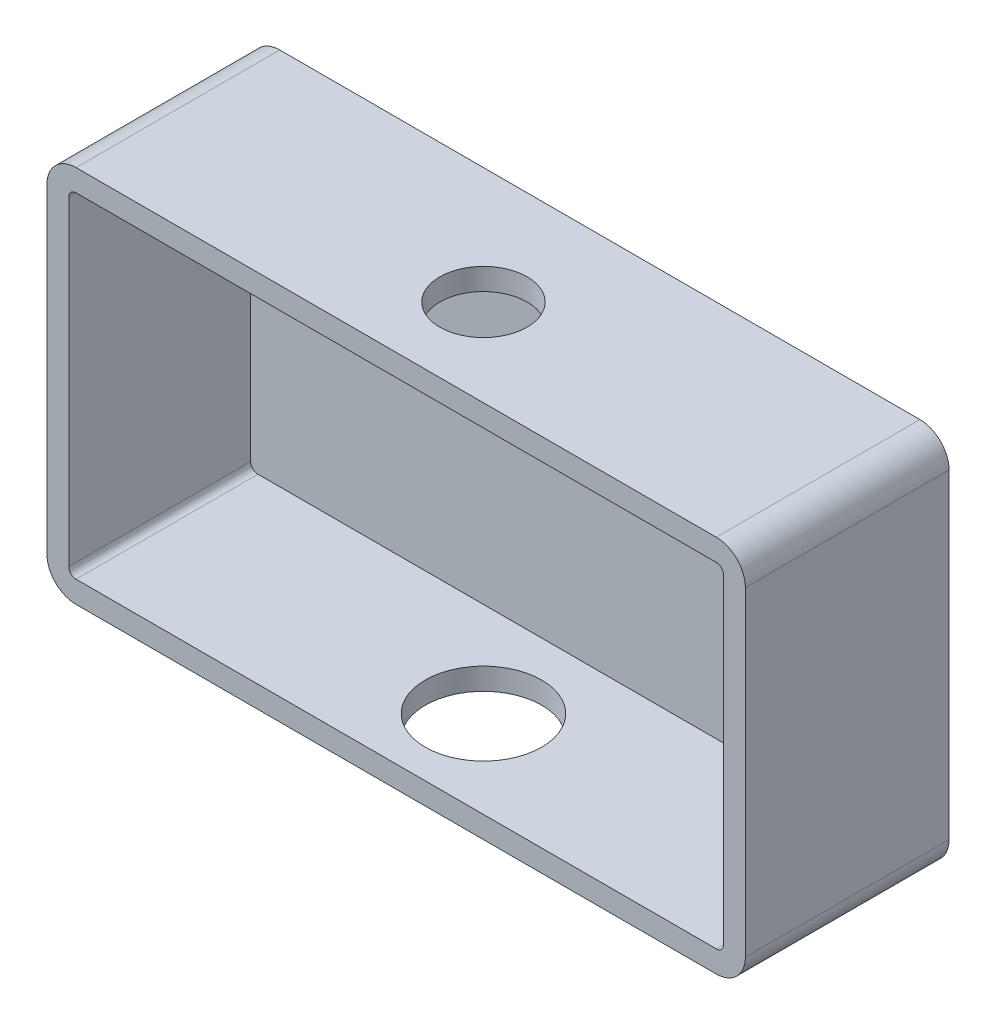
SolidWorks part; units mm, degrees
ref_plane "前视基准面" through (0, 0, 0) normal (0, 0, 1) x (1, 0, 0)
ref_plane "上视基准面" through (0, 0, 0) normal (0, 1, 0) x (1, 0, 0)
ref_plane "右视基准面" through (0, 0, 0) normal (1, 0, 0) x (0, 0, -1)
other "Configuration Table"
sketch "草图1" plane through (0, 0, 0) normal (0, 0, 1) x (1, 0, 0)
  line L0 (0, 0) -> (48, 0)
  line L1 (48, 0) -> (48, 26)
  line L2 (48, 26) -> (0, 26)
  line L3 (0, 26) -> (0, 0)
  dimension "width" = 48
  dimension "height" = 26
extrude "Enclosure" add sketch "草图1" along normal blind 14
fillet "Fillet" radius 2 4 edges at (0, 26, 7) (48, 26, 7) (48, 0, 7) (0, 0, 7)
shell "抽壳1" thickness 1.5
sketch "草图2" plane through (0, 0, 0) normal (0, -1, 0) x (1, 0, 0)
  circle A0 centre (24, 8) radius 3
  dimension "diameter" = 6
  dimension "x" = 24
  dimension "y" = 8
extrude "Cable_entry" cut sketch "草图2" against normal through all
sketch "草图3" plane through (0, 0, 0) normal (0, -1, 0) x (1, 0, 0)
  circle A0 centre (24, 8) radius 4
  dimension "diameter" = 8
  dimension "x" = 24
  dimension "y" = 8
extrude "Cable_entry_relief" cut sketch "草图3" against normal blind 1.6
